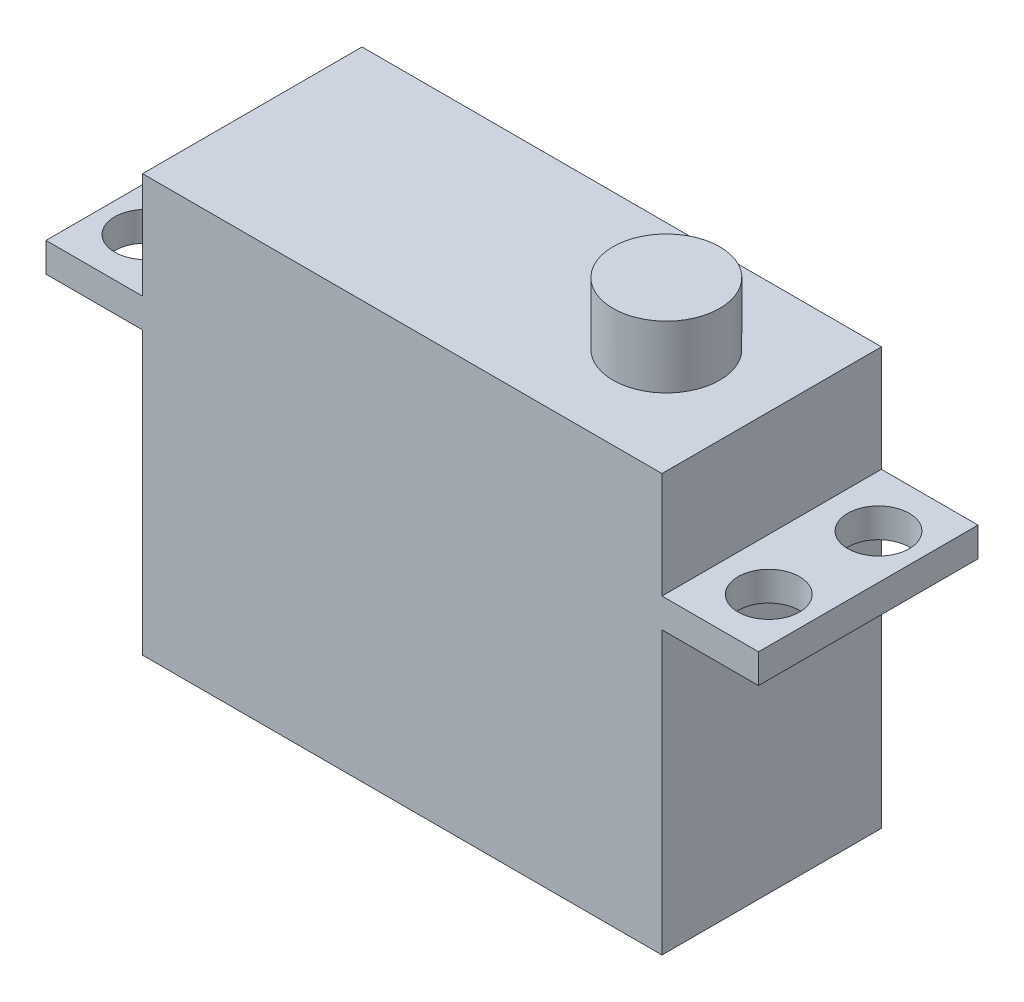
SolidWorks part; units mm, degrees
ref_plane "前视基准面" through (0, 0, 0) normal (0, 0, 1) x (1, 0, 0)
ref_plane "上视基准面" through (0, 0, 0) normal (0, 1, 0) x (1, 0, 0)
ref_plane "右视基准面" through (0, 0, 0) normal (1, 0, 0) x (0, 0, -1)
other "Configuration Table"
sketch "草图1" plane through (0, 0, 0) normal (0, 1, 0) x (1, 0, 0)
  line L1 (0, 0) -> (35.5, 0)
  line L2 (0, 0) -> (0, 15)
  line L3 (0, 15) -> (35.5, 15)
  line L4 (35.5, 0) -> (35.5, 15)
extrude "凸台-拉伸1" add sketch "草图1" along normal blind 19.25
sketch "草图2" plane through (0, 19.25, 0) normal (0, 1, 0) x (1, 0, 0)
  line L0 (0, 15) -> (35.5, 0) construction
  line L1 (17.75, 7.5) -> (39.05, 7.5) construction
  line L2 (-6.6, 0) -> (42.1, 0)
  line L3 (-6.6, 0) -> (-6.6, 15)
  line L4 (0, 15) -> (0, 0)
  line L5 (0, 0) -> (35.5, 0)
  line L6 (35.5, 0) -> (35.5, 15)
  line L7 (35.5, 15) -> (0, 15)
  line L8 (0, 15) -> (0, 0)
  line L9 (0, 0) -> (35.5, 0)
  line L10 (35.5, 0) -> (35.5, 15)
  line L11 (35.5, 15) -> (0, 15)
  line L12 (-6.6, 15) -> (42.1, 15)
  line L13 (42.1, 0) -> (42.1, 15)
  line L14 (-6.6, 0) -> (42.1, 15) construction
  line L15 (-6.6, 15) -> (42.1, 0) construction
  line L16 (39.05, 11.25) -> (39.05, 3.75) construction
  line L17 (17.75, 7.5) -> (17.75, 11.25) construction
  circle A0 centre (39.05, 3.75) radius 2.1
  circle A1 centre (39.05, 11.25) radius 2.1
  circle A2 centre (-3.55, 3.75) radius 2.1
  circle A3 centre (-3.55, 11.25) radius 2.1
  point P2 (17.75, 7.5)
  point P13 (39.05, 7.5)
  line M5 (0, 15) -> (0, 0)
  line M6 (0, 0) -> (35.5, 0)
  line M7 (35.5, 0) -> (35.5, 15)
  line M8 (35.5, 15) -> (0, 15)
  dimension "D1" = 0
extrude "凸台-拉伸2" add sketch "草图2" along normal blind 2 contours M8 M5 M6 M7 | L2 L13 L12 A0 A1 M7 | L12 L3 L2 A3 A2 M5
sketch "草图3" plane through (0, 21.25, 0) normal (0, 1, 0) x (1, 0, 0)
  line L4 (0, 15) -> (0, 0)
  line L5 (35.5, 15) -> (0, 15)
  line L6 (35.5, 0) -> (35.5, 15)
  line L7 (0, 0) -> (35.5, 0)
  line L8 (0, 15) -> (0, 0)
  line L9 (35.5, 15) -> (0, 15)
  line L10 (35.5, 0) -> (35.5, 15)
  line L11 (0, 0) -> (35.5, 0)
  dimension "D1" = 0
extrude "凸台-拉伸3" add sketch "草图3" along normal blind 7.25
sketch "草图4" plane through (0, 28.5, 0) normal (0, 1, 0) x (1, 0, 0)
  line L0 (-3.55, 11.25) -> (28.3, 11.25) construction
  line L1 (28.3, 15) -> (28.3, 0) construction
  line L2 (35.5, 15) -> (0, 15) construction
  line L3 (0, 0) -> (35.5, 0) construction
  circle A0 centre (28.3, 7.5) radius 3.6496
extrude "凸台-拉伸4" add sketch "草图4" along normal offset from surface (4.25 mm away) 32.75 up to face at (17.75, 0, -7.5)
